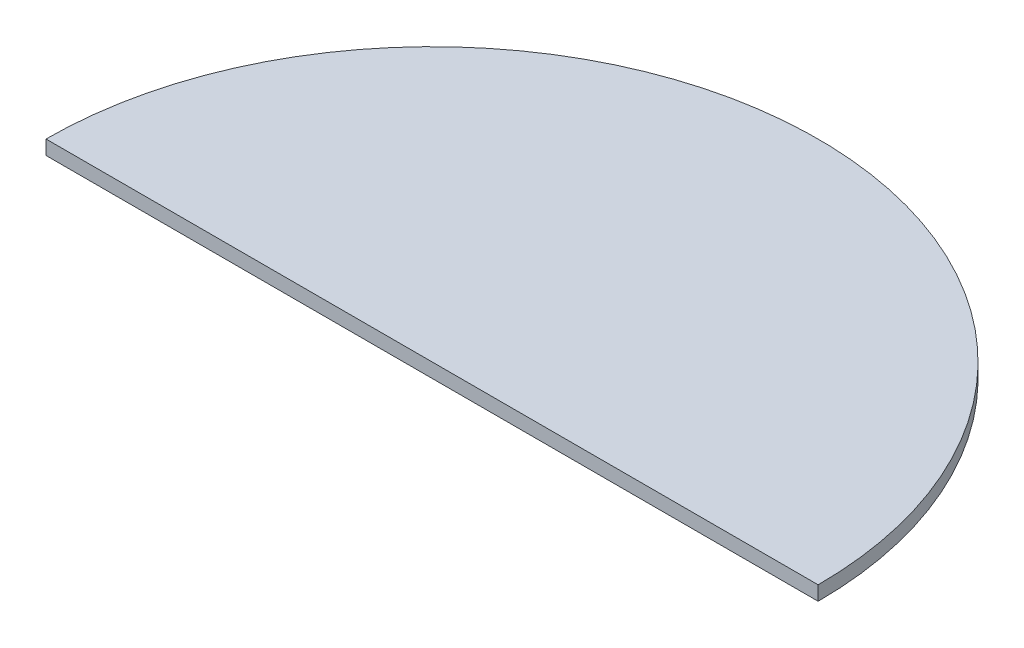
SolidWorks part; units mm, degrees
material "Brass"
ref_plane "Front Plane" through (0, 0, 0) normal (0, 0, 1) x (1, 0, 0)
ref_plane "Top Plane" through (0, 0, 0) normal (0, 1, 0) x (1, 0, 0)
ref_plane "Right Plane" through (0, 0, 0) normal (1, 0, 0) x (0, 0, -1)
sketch "Sketch2" plane through (0, 0, 0) normal (0, 1, 0) x (1, 0, 0)
  line L0 (-13.5, 0) -> (13.5, 0)
  arc A0 (13.5, 0) -> (-13.5, 0) centre (0, 0) ccw
  dimension "D1" = 27
extrude "Boss-Extrude1" add sketch "Sketch2" along normal blind 0.5
